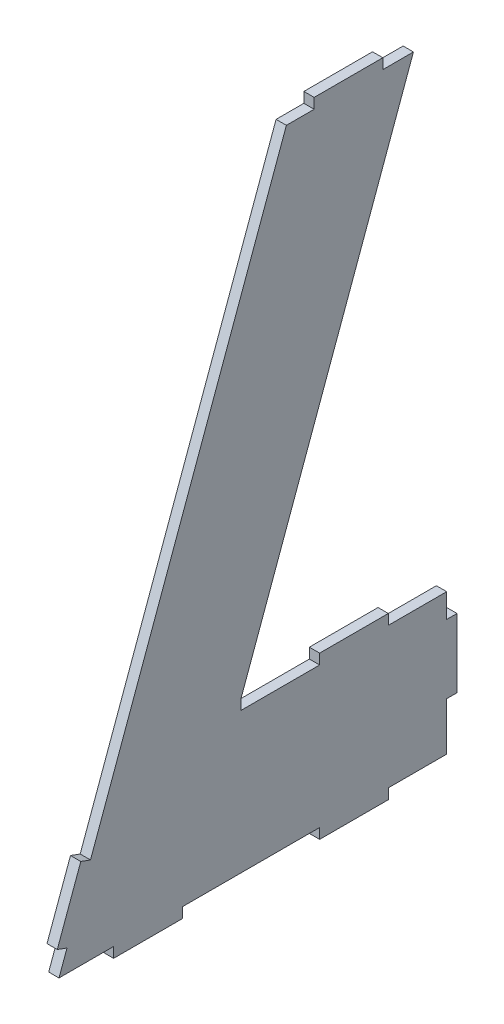
SolidWorks part; units mm, degrees
ref_plane "Front Plane" through (0, 0, 0) normal (0, 0, 1) x (1, 0, 0)
ref_plane "Top Plane" through (0, 0, 0) normal (0, 1, 0) x (1, 0, 0)
ref_plane "Right Plane" through (0, 0, 0) normal (1, 0, 0) x (0, 0, -1)
sketch "Sketch1" plane through (0, 0, 0) normal (1, 0, 0) x (0, 0, -1)
  line L0 (0, 0) -> (120, 0)
  line L1 (0, 0) -> (68.404, 187.9385)
  line L2 (120, 0) -> (188.404, 187.9385)
  line L3 (68.404, 187.9385) -> (188.404, 187.9385)
  dimension "D1" = 200
  dimension "D2" = 120
  dimension "D3" = 70
extrude "Boss-Extrude1" add sketch "Sketch1" along normal blind 3
sketch "Sketch2" plane through (3, 0, 0) normal (1, 0, 0) x (0, 0, -1)
  line L0 (188.404, 187.9385) -> (137.101, 46.9846)
  line L1 (188.404, 187.9385) -> (108.404, 187.9385)
  line L2 (137.101, 46.9846) -> (57.101, 46.9846)
  line L3 (108.404, 187.9385) -> (57.101, 46.9846)
  line L4 (120, 0) -> (188.404, 187.9385) construction
  dimension "D1" = 80
  dimension "D2" = 150
  dimension "D3" = 70
extrude "Cut-Extrude1" cut sketch "Sketch2" against normal through all
sketch "Sketch3" plane through (3, 0, 0) normal (1, 0, 0) x (0, 0, -1)
  line L1 (120, 0) -> (149.9768, 0)
  line L2 (120, 0) -> (120, 52.2685)
  line L3 (120, 52.2685) -> (149.9768, 52.2685)
  line L4 (149.9768, 0) -> (149.9768, 52.2685)
extrude "Cut-Extrude2" cut sketch "Sketch3" against normal through all
sketch "Sketch5" plane through (3, 0, 0) normal (1, 0, 0) x (0, 0, -1)
  line L0 (108.404, 187.9385) -> (68.404, 187.9385) construction
  line L1 (78.404, 187.9385) -> (67.3121, 187.9385)
  line L2 (78.404, 187.9385) -> (78.404, 184.9385)
  line L3 (78.404, 184.9385) -> (67.3121, 184.9385)
  line L4 (67.3121, 187.9385) -> (67.3121, 184.9385)
  line L5 (68.404, 187.9385) -> (0, 0) construction
  line L7 (108.404, 187.9385) -> (98.404, 187.9385)
  line L8 (108.404, 187.9385) -> (108.404, 184.9385)
  line L9 (108.404, 184.9385) -> (98.404, 184.9385)
  line L10 (98.404, 187.9385) -> (98.404, 184.9385)
  dimension "D1" = 3
  dimension "D2" = 10
  dimension "D3" = 3
  dimension "D4" = 10
  dimension "D5" = 20
extrude "Cut-Extrude4" cut sketch "Sketch5" against normal through all
sketch "Sketch6" plane through (3, 0, 0) normal (1, 0, 0) x (0, 0, -1)
  line L1 (120, 0) -> (100, 0)
  line L2 (120, 0) -> (120, 3)
  line L3 (120, 3) -> (100, 3)
  line L4 (100, 0) -> (100, 3)
  line L5 (0, 0) -> (20, 0)
  line L6 (0, 0) -> (0, 3)
  line L7 (0, 3) -> (20, 3)
  line L8 (20, 0) -> (20, 3)
  dimension "D1" = 3
  dimension "D2" = 3
  dimension "D3" = 20
  dimension "D4" = 20
extrude "Cut-Extrude5" cut sketch "Sketch6" against normal through all
sketch "Sketch7" plane through (3, 0, 0) normal (1, 0, 0) x (0, 0, -1)
  line L0 (20, 0) -> (100, 0) construction
  line L1 (40, 0) -> (80, 0)
  line L2 (40, 0) -> (40, 3)
  line L3 (40, 3) -> (80, 3)
  line L4 (80, 0) -> (80, 3)
  line L5 (20, 0) -> (20, 3) construction
  line L6 (100, 3) -> (100, 0) construction
  dimension "D1" = 3
  dimension "D2" = 40
  dimension "D3" = 20
  dimension "D4" = 20
extrude "Cut-Extrude6" cut sketch "Sketch7" against normal through all
sketch "Sketch8" plane through (3, 0, 0) normal (1, 0, 0) x (0, 0, -1)
  line L1 (120, 46.9846) -> (100, 46.9846)
  line L2 (120, 46.9846) -> (120, 43.9846)
  line L3 (120, 43.9846) -> (100, 43.9846)
  line L4 (100, 46.9846) -> (100, 43.9846)
  line L5 (57.101, 46.9846) -> (80, 46.9846)
  line L6 (57.101, 46.9846) -> (57.101, 43.9846)
  line L7 (57.101, 43.9846) -> (80, 43.9846)
  line L8 (80, 46.9846) -> (80, 43.9846)
  dimension "D1" = 3
  dimension "D2" = 3
  dimension "D3" = 20
  dimension "D4" = 20
extrude "Cut-Extrude7" cut sketch "Sketch8" against normal through all
sketch "Sketch10" plane through (3, 0, 0) normal (1, 0, 0) x (0, 0, -1)
  line L1 (120, 43.9846) -> (117, 43.9846)
  line L2 (120, 43.9846) -> (120, 36.9846)
  line L3 (120, 36.9846) -> (117, 36.9846)
  line L4 (117, 43.9846) -> (117, 36.9846)
  line L5 (120, 3) -> (117, 3)
  line L6 (120, 3) -> (120, 16.9846)
  line L7 (120, 16.9846) -> (117, 16.9846)
  line L8 (117, 3) -> (117, 16.9846)
  dimension "D1" = 3
  dimension "D2" = 3
  dimension "D3" = 7
  dimension "D4" = 20
extrude "Cut-Extrude9" cut sketch "Sketch10" against normal through all
sketch "Sketch11" plane through (0, 0, 0) normal (-1, 0, 0) x (0, 0, 1)
  line L0 (-67.3121, 184.9385) -> (-1.0919, 3)
  line L1 (-67.3121, 184.9385) -> (-70.3121, 184.9385)
  line L2 (-1.0919, 3) -> (-4.0919, 3)
  line L3 (-70.3121, 184.9385) -> (-4.0919, 3)
  line L4 (-20, 3) -> (-1.0919, 3) construction
  dimension "D1" = 3
extrude "Cut-Extrude10" cut sketch "Sketch11" against normal up to next
sketch "Sketch12" plane through (0, -0.9642, -2.6491) normal (0, 0.342, 0.9397) x (1, 0, 0)
  line L0 (0, 197.8335) -> (0, 4.2186) construction
  line L1 (0, 31.0261) -> (3, 31.0261)
  line L2 (0, 31.0261) -> (0, 11.0261)
  line L3 (0, 11.0261) -> (3, 11.0261)
  line L4 (3, 31.0261) -> (3, 11.0261)
  line L5 (3, 4.2186) -> (3, 197.8335) construction
  line L6 (3, 4.2186) -> (0, 4.2186) construction
  dimension "D1" = 20
  dimension "D2" = 6.8075
extrude "Boss-Extrude2" add sketch "Sketch12" along normal blind 3
